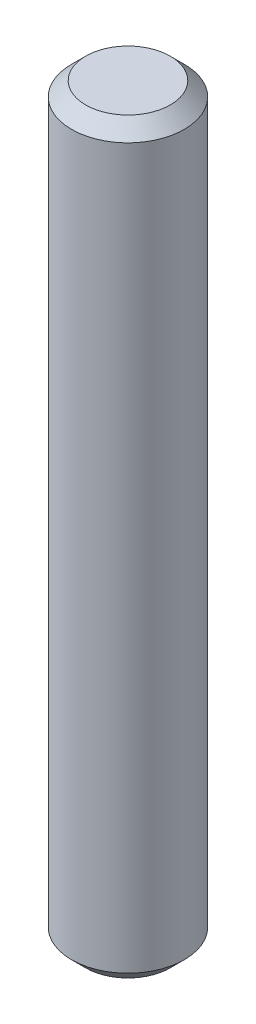
SolidWorks part; units mm, degrees
ref_plane "Front Plane" through (0, 0, 0) normal (0, 0, 1) x (1, 0, 0)
ref_plane "Top Plane" through (0, 0, 0) normal (0, 1, 0) x (1, 0, 0)
ref_plane "Right Plane" through (0, 0, 0) normal (1, 0, 0) x (0, 0, -1)
sketch "Sketch1" plane through (0, 0, 0) normal (0, 1, 0) x (1, 0, 0)
  circle A0 centre (0, 0) radius 4
  dimension "D1" = 8
extrude "Boss-Extrude1" add sketch "Sketch1" along normal blind 53
chamfer "Chamfer1" distance 1 angle 45 2 edges at (0, 0, 4) (0, 53, 4)
